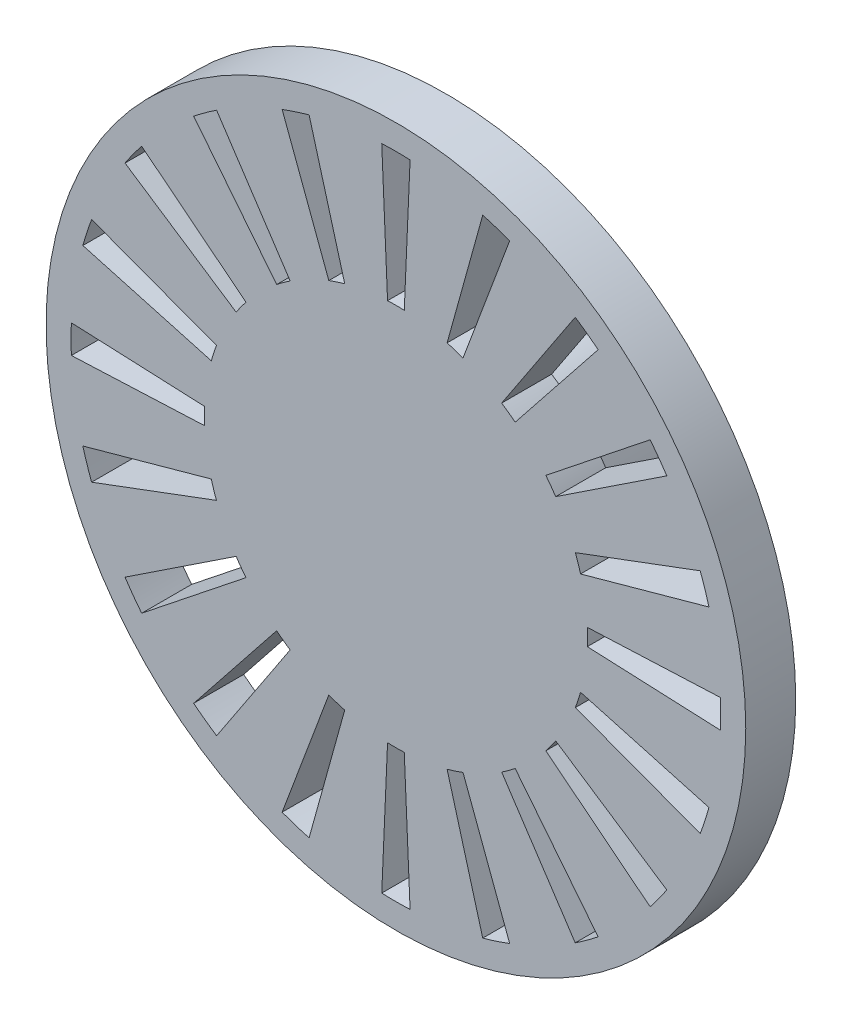
SolidWorks part; units mm, degrees
ref_plane "Plano frontal" through (0, 0, 0) normal (0, 0, 1) x (1, 0, 0)
ref_plane "Plano superior" through (0, 0, 0) normal (0, 1, 0) x (1, 0, 0)
ref_plane "Plano direito" through (0, 0, 0) normal (1, 0, 0) x (0, 0, -1)
sketch "Esboço1" plane through (0, 0, 0) normal (0, 0, 1) x (1, 0, 0)
  circle A0 centre (0, 0) radius 21
  dimension "D2" = 42
extrude "Ressalto-extrusão1" add sketch "Esboço1" along normal blind 3
sketch "Esboço5" plane through (0, 0, 3) normal (0, 0, 1) x (1, 0, 0)
  line L0 (0, 0) -> (0, 21) construction
  line L5 (-0.5016, 11.4891) -> (-0.8506, 19.4814)
  line L6 (0.5016, 11.4891) -> (0.8506, 19.4814)
  circle A0 centre (0, 0) radius 21 construction
  arc A1 (0.8506, 19.4814) -> (-0.8506, 19.4814) centre (0, 0) ccw
  arc A2 (0.5016, 11.4891) -> (-0.5016, 11.4891) centre (0, 0) ccw
  dimension "D3" = 39
  dimension "D4" = 23
  dimension "D1" = 2.5
  dimension "D2" = 2.5
extrude "Corte-extrusão1" cut sketch "Esboço5" against normal through all
pattern_circular "PadrãoCircular1" count 20 over 360 about axis through (0, 0, 0) along (0, 0, 1) of "Corte-extrusão1"
sketch "Esboço7" plane through (0, 0, 0) normal (0, 0, -1) x (-1, 0, 0)
  circle A0 centre (0, 0) radius 6
  dimension "D1" = 12
extrude "Ressalto-extrusão2" add sketch "Esboço7" along normal blind 10
chamfer "Chanfro1" distance 3 angle 45 1 edges at (-6, 0, -10)
sketch "Esboço8" plane through (0, 0, -10) normal (0, 0, -1) x (-1, 0, 0)
  circle A0 centre (0, 0) radius 1.3
  dimension "D1" = 2.6
extrude "Corte-extrusão3" cut sketch "Esboço8" against normal offset from surface (12 mm away) 1 up to face at (-15.4926, 0, 3)
